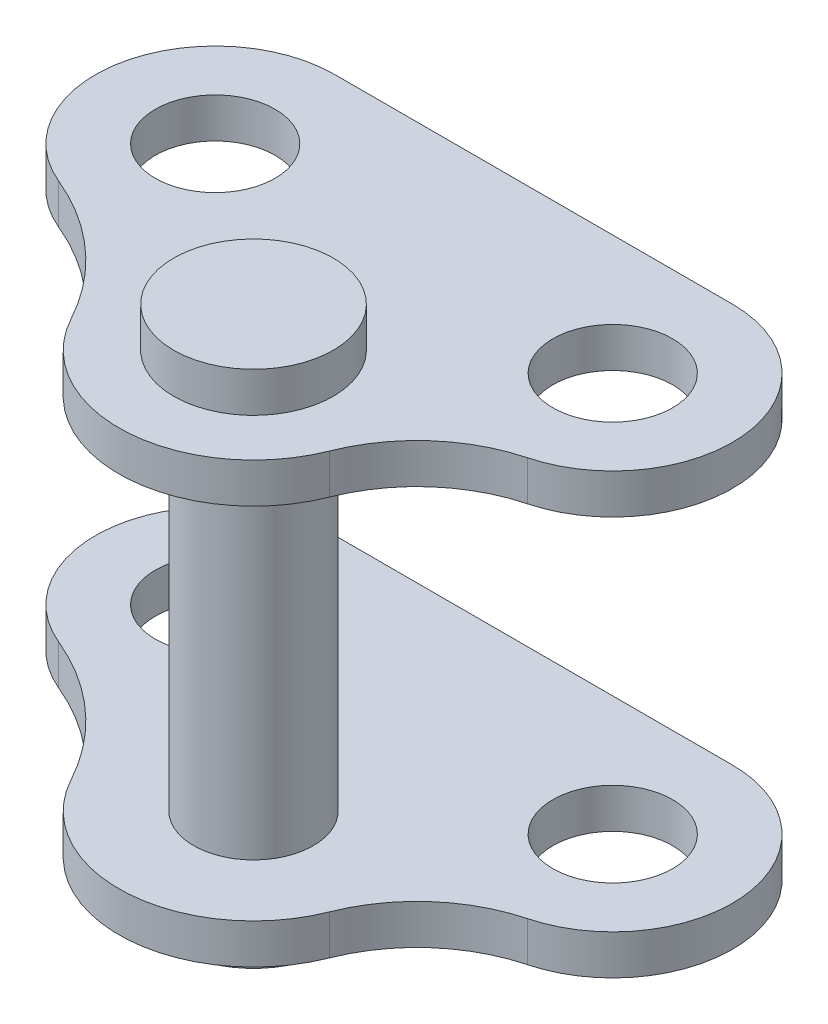
SolidWorks part; units mm, degrees
ref_plane "Front Plane" through (0, 0, 0) normal (0, 0, 1) x (1, 0, 0)
ref_plane "Top Plane" through (0, 0, 0) normal (0, 1, 0) x (1, 0, 0)
ref_plane "Right Plane" through (0, 0, 0) normal (1, 0, 0) x (0, 0, -1)
sketch "Sketch1" plane through (0, 0, 0) normal (0, 1, 0) x (1, 0, 0)
  line L0 (-6.35, 4.7625) -> (9.398, 4.7621)
  circle A0 centre (-6.35, 0) radius 2.3813
  circle A1 centre (9.4615, 0) radius 2.3813
  circle A2 centre (-6.35, 0) radius 4.7625
  circle A3 centre (9.4615, 0) radius 4.7625
  circle A4 centre (1.524, -6.35) radius 2.3812
  circle A5 centre (1.524, -6.35) radius 5.353
  arc A6 (-8.1764, -4.3984) -> (-3.1815, -8.9019) centre (-12.0416, -13.707) cw
  arc A7 (6.5046, -8.3115) -> (10.6745, -4.6054) centre (12.2461, -10.5726) cw
  dimension "D1" = 4.7625
  dimension "D2" = 6.35
  dimension "D3" = 0
  dimension "D5" = 4.7625
  dimension "D6" = 9.525
  dimension "D7" = 9.525
  dimension "D8" = 4.7625
  dimension "D9" = 7.874
  dimension "D10" = 6.35
  dimension "D4" = 15.8115
extrude "Boss-Extrude1" add sketch "Sketch1" along normal blind 1.5875 contours A2 A0 | A2 A6 A5 | A5 A3 L0 A2 | A3 A1 | A5 A7 A3 | A5 A4
sketch "Sketch2" plane through (0, 0, 0) normal (0, -1, 0) x (1, 0, 0)
  circle A0 centre (1.524, 6.35) radius 3.175
  dimension "D1" = 6.35
extrude "Boss-Extrude2" add sketch "Sketch2" along normal blind 1.5875
sketch "Sketch3" plane through (0, 0, 0) normal (0, 1, 0) x (1, 0, 0)
  circle A0 centre (1.524, -6.35) radius 2.3812
extrude "Boss-Extrude3" add sketch "Sketch3" along normal blind 19.05
sketch "Sketch4" plane through (0, 19.05, 0) normal (0, 1, 0) x (1, 0, 0)
  circle A0 centre (1.524, -6.35) radius 3.175
  dimension "D1" = 6.35
extrude "Boss-Extrude4" add sketch "Sketch4" against normal blind 1.5875
sketch "Sketch5" plane through (0, 17.4625, 0) normal (0, -1, 0) x (1, 0, 0)
  line L0 (-6.35, -4.7625) -> (9.4615, -4.7625)
  circle A0 centre (-6.35, 0) radius 2.3813
  circle A1 centre (9.4615, 0) radius 2.3813
  circle A2 centre (1.524, 6.35) radius 5.353
  circle A3 centre (-6.35, 0) radius 4.7625
  circle A4 centre (9.4615, 0) radius 4.7625
  arc A5 (-8.1764, 4.3984) -> (-3.1815, 8.9019) centre (-12.0416, 13.707) ccw
  arc A6 (6.5046, 8.3115) -> (10.6745, 4.6054) centre (12.2461, 10.5726) ccw
  circle M1 centre (1.524, 6.35) radius 2.3812
  circle M2 centre (1.524, 6.35) radius 3.175
extrude "Boss-Extrude5" add sketch "Sketch5" along normal blind 1.5875 separate body contours A2 M2 | A6 A2 A4 | A4 A1 | A5 A3 A2 | A4 A2 A3 L0 | A3 A0 | M2 M1
